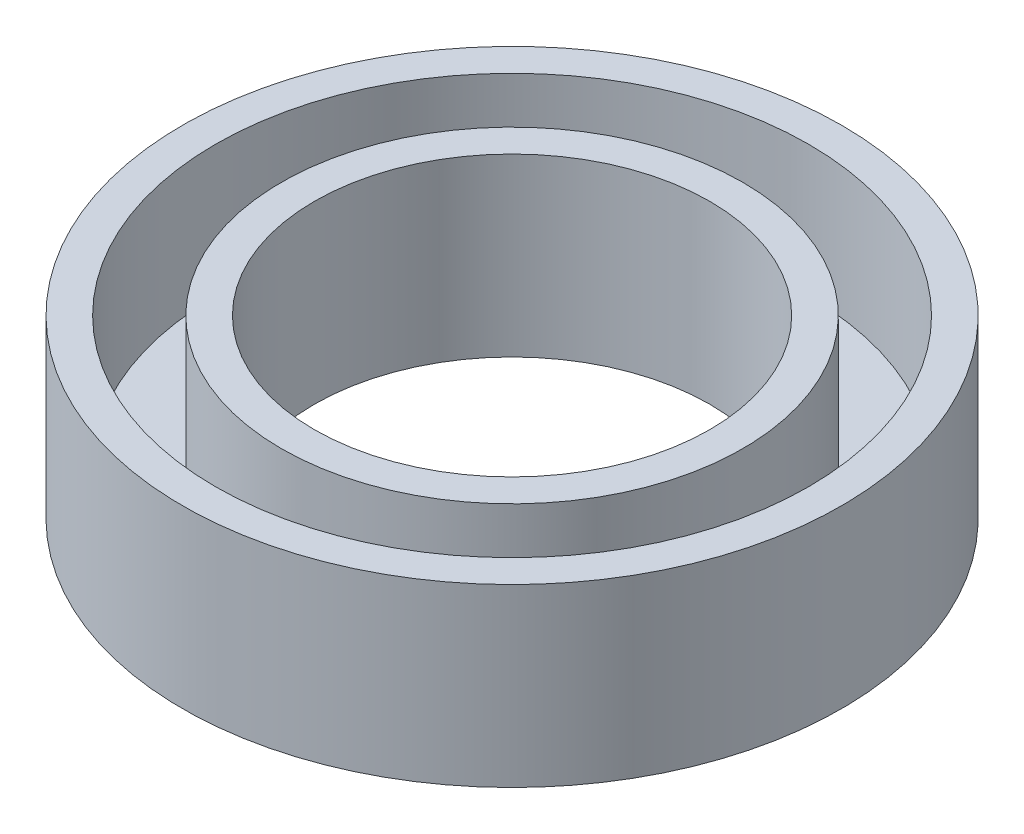
SolidWorks part; units mm, degrees
ref_plane "前视基准面" through (0, 0, 0) normal (0, 0, 1) x (1, 0, 0)
ref_plane "上视基准面" through (0, 0, 0) normal (0, 1, 0) x (1, 0, 0)
ref_plane "右视基准面" through (0, 0, 0) normal (1, 0, 0) x (0, 0, -1)
sketch "草图1" plane through (0, 0, 0) normal (0, 0, 1) x (1, 0, 0)
  line L0 (0, 0) -> (0, 29.352) construction
  line L1 (-13.5, 8) -> (-10.5, 8)
  line L2 (-13.5, 8) -> (-13.5, 2)
  line L3 (-13.5, 2) -> (-10.5, 2)
  line L4 (-10.5, 8) -> (-10.5, 2)
  line L5 (-13.5, 8) -> (-10.5, 2) construction
  line L6 (-13.5, 2) -> (-10.5, 8) construction
  line L7 (-15, 0) -> (-9, 0)
  line L8 (-15, 0) -> (-15, 8)
  line L9 (-15, 8) -> (-9, 8)
  line L10 (-9, 0) -> (-9, 8)
  line L11 (-15, 0) -> (-9, 8) construction
  line L12 (-15, 8) -> (-9, 0) construction
  line L13 (-9, 0) -> (0, 0) construction
  point P0 (-12, 5)
  point P5 (-12, 4)
  point P13 (-10.5, 3.6295)
  dimension "D1" = 1.5
  dimension "D2" = 1.5
  dimension "D3" = 8
  dimension "D4" = 9
  dimension "D5" = 15
  dimension "D6" = 2
revolve "旋转1" add sketch "草图1" angle 360 about L0
